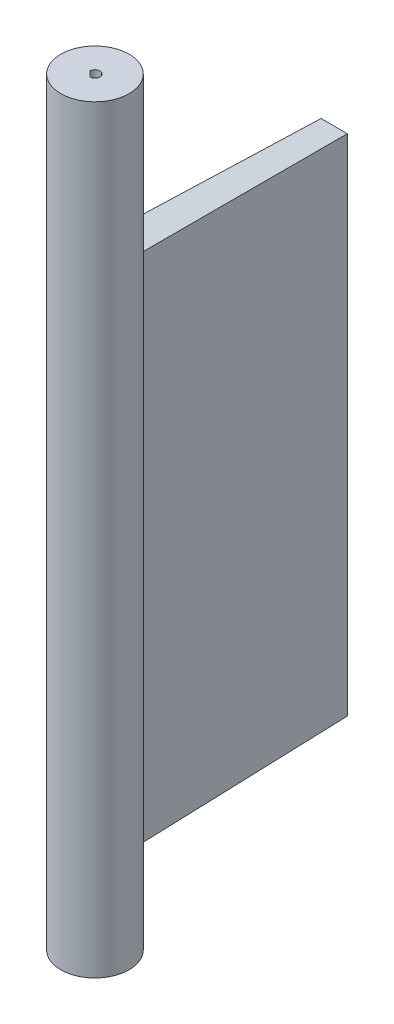
SolidWorks part; units mm, degrees
material "1.0715 (11SMn30)"
ref_plane "Ebene vorne" through (0, 0, 0) normal (0, 0, 1) x (1, 0, 0)
ref_plane "Ebene oben" through (0, 0, 0) normal (0, 1, 0) x (1, 0, 0)
ref_plane "Ebene rechts" through (0, 0, 0) normal (1, 0, 0) x (0, 0, -1)
sketch "Skizze2" plane through (0, 0, 0) normal (0, 1, 0) x (1, 0, 0)
  circle A0 centre (0, 0) radius 10
  dimension "D1" = 20
extrude "Aufsatz-Linear austragen1" add sketch "Skizze2" along normal blind 210
sketch "Skizze7" plane through (0, 0, 0) normal (0, 0, 1) x (1, 0, 0)
  line L0 (-10, 0) -> (10, 0) construction
  line L1 (5.067, 175) -> (-5.067, 175)
  line L2 (5.067, 175) -> (5.067, 25)
  line L3 (5.067, 25) -> (-5.067, 25)
  line L4 (-5.067, 175) -> (-5.067, 25)
  line L5 (5.067, 175) -> (-5.067, 25) construction
  line L6 (5.067, 25) -> (-5.067, 175) construction
  point P0 (0, 100)
  dimension "D1" = 150
  dimension "D2" = 25
extrude "Aufsatz-Linear austragen2" add sketch "Skizze7" against normal blind 70 draft 1
sketch "Skizze8" plane through (0, 210, 0) normal (0, 1, 0) x (1, 0, 0)
  circle A0 centre (0, 0) radius 10
extrude "Aufsatz-Linear austragen3" add sketch "Skizze8" along normal blind 12
sketch "Skizze9" plane through (0, 222, 0) normal (0, 1, 0) x (1, 0, 0)
  line L0 (0, -1.5) -> (-1.5, 0)
  arc A1 (0, -1.5) -> (-1.5, 0) centre (0, 0) ccw
  point P1 (0, 0)
extrude "Schnitt-Linear austragen1" cut sketch "Skizze9" against normal blind 10
